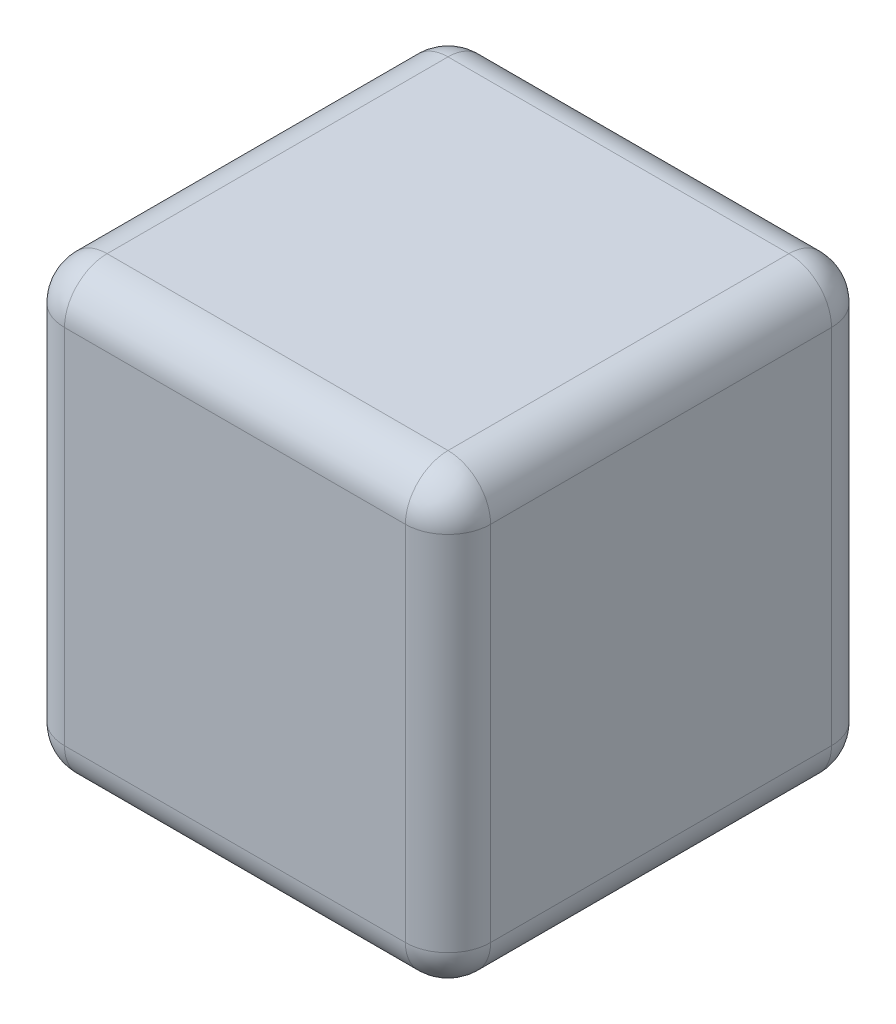
SolidWorks part; units mm, degrees
ref_plane "Front" through (0, 0, 0) normal (0, 0, 1) x (1, 0, 0)
ref_plane "Top" through (0, 0, 0) normal (0, 1, 0) x (1, 0, 0)
ref_plane "Right" through (0, 0, 0) normal (1, 0, 0) x (0, 0, -1)
sketch "Sketch1" plane through (0, 0, 0) normal (0, 1, 0) x (1, 0, 0)
  line L1 (0, 0) -> (100, 0)
  line L2 (0, 0) -> (0, 100)
  line L3 (0, 100) -> (100, 100)
  line L4 (100, 0) -> (100, 100)
  dimension "D1" = 100
  dimension "D2" = 100
extrude "Boss-Extrude1" add sketch "Sketch1" along normal blind 105
fillet "Fillet1" radius 10 12 edges at (50, 0, -100) (0, 52.5, -100) (0, 0, -50) (0, 52.5, 0) (50, 0, 0) (50, 105, -100) (50, 105, 0) (0, 105, -50) (100, 52.5, 0) (100, 105, -50) (100, 52.5, -100) (100, 0, -50)
